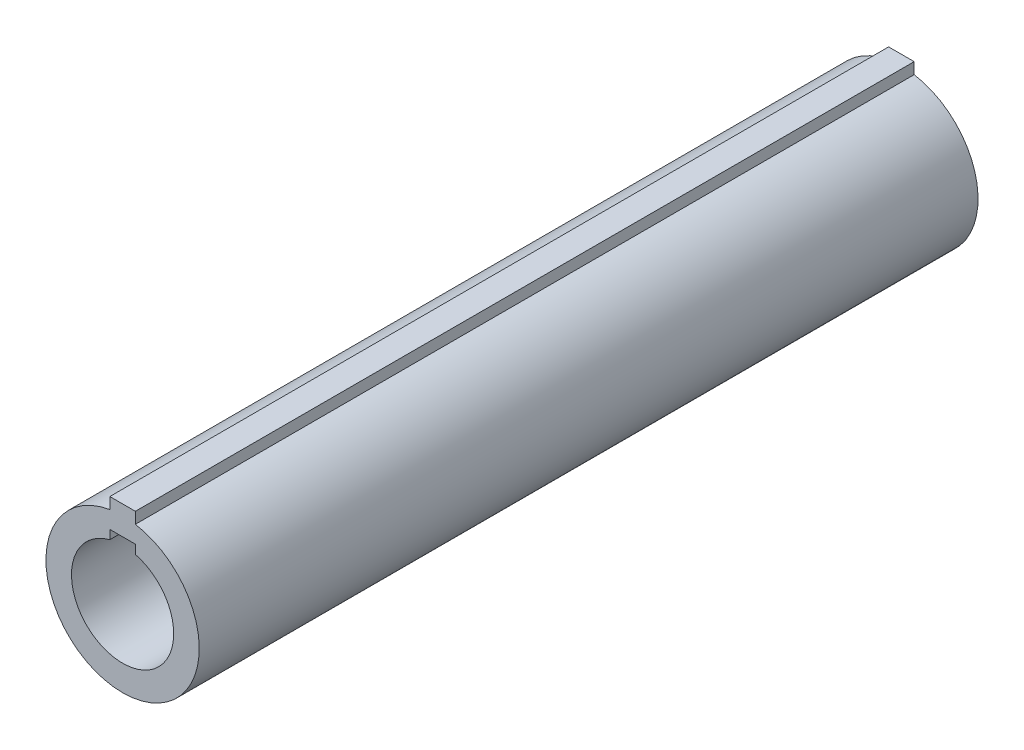
SolidWorks part; units mm, degrees
ref_plane "Front Plane" through (0, 0, 0) normal (0, 0, 1) x (1, 0, 0)
ref_plane "Top Plane" through (0, 0, 0) normal (0, 1, 0) x (1, 0, 0)
ref_plane "Right Plane" through (0, 0, 0) normal (1, 0, 0) x (0, 0, -1)
sketch "Sketch1" plane through (0, 0, 0) normal (0, 0, 1) x (1, 0, 0)
  line L0 (-2.5, 9.6825) -> (-2.5, 11.43)
  line L1 (-2.5, 11.43) -> (2.5, 11.43)
  line L2 (2.5, 11.43) -> (2.5, 9.6825)
  line L3 (-2.5, 14.7902) -> (-2.5, 17)
  line L4 (-2.5, 17) -> (2.5, 17)
  line L5 (2.5, 17) -> (2.5, 14.7902)
  arc A0 (-2.5, 14.7902) -> (2.5, 14.7902) centre (0, 0) ccw
  arc A1 (-2.5, 9.6825) -> (2.5, 9.6825) centre (0, 0) ccw
  point P6 (0, 11.43)
  point P12 (0, 17)
  dimension "D1" = 20
  dimension "D2" = 30
  dimension "D3" = 11.43
  dimension "D4" = 5
  dimension "D5" = 17
extrude "Boss-Extrude1" add sketch "Sketch1" along normal blind 152.4 contours A1 L2 L1 L0 | A0 L5 L4 L3
